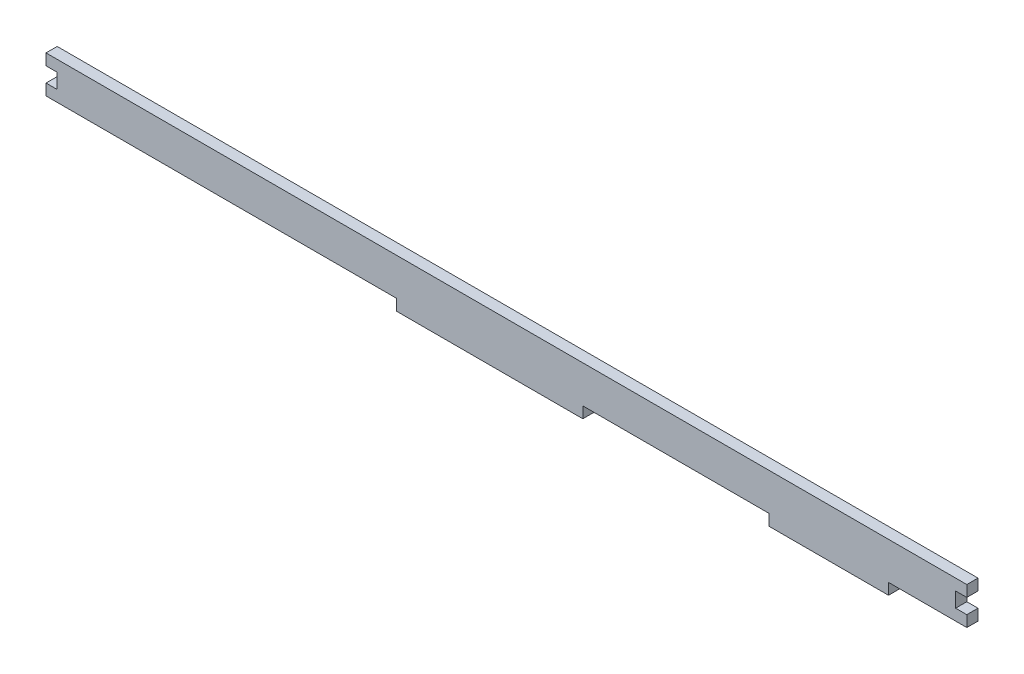
SolidWorks part; units mm, degrees
ref_plane "Front Plane" through (0, 0, 0) normal (0, 0, 1) x (1, 0, 0)
ref_plane "Top Plane" through (0, 0, 0) normal (0, 1, 0) x (1, 0, 0)
ref_plane "Right Plane" through (0, 0, 0) normal (1, 0, 0) x (0, 0, -1)
sketch "Sketch1" plane through (0, 0, 0) normal (0, 0, 1) x (1, 0, 0)
  line L0 (144, 0) -> (194, 0)
  line L1 (0, 0) -> (94, 0)
  line L2 (0, 10) -> (244, 10)
  line L3 (0, 3) -> (0, 0)
  line L4 (244, 7) -> (244, 3)
  line L5 (0, 7) -> (3, 7)
  line L6 (94, 0) -> (94, -3)
  line L7 (94, -3) -> (144, -3)
  line L8 (144, 0) -> (144, -3)
  line L9 (244, 10) -> (247, 10)
  line L10 (194, 0) -> (194, -3)
  line L11 (194, -3) -> (226, -3)
  line L12 (226, 0) -> (226, -3)
  line L14 (244, 7) -> (247, 7)
  line L15 (247, 10) -> (247, 7)
  line L16 (226, 0) -> (247, 0)
  line L18 (244, 3) -> (247, 3)
  line L19 (247, 0) -> (247, 3)
  line L22 (0, 3) -> (3, 3)
  line L23 (3, 7) -> (3, 3)
  line L25 (0, 10) -> (0, 7)
  dimension "D1" = 50
  dimension "D2" = 32
  dimension "D3" = 3
  dimension "D4" = 3
  dimension "D5" = 50
  dimension "D6" = 3
  dimension "D7" = 3
  dimension "D8" = 10
  dimension "D9" = 3
  dimension "D10" = 21
  dimension "D11" = 3
  dimension "D12" = 3
  dimension "D13" = 3
  dimension "D14" = 3
  dimension "D15" = 94
  dimension "D16" = 0
  dimension "D17" = 3
  dimension "D18" = 4
  dimension "D19" = 3
  dimension "D20" = 4
extrude "Boss-Extrude1" add sketch "Sketch1" along normal blind 3
